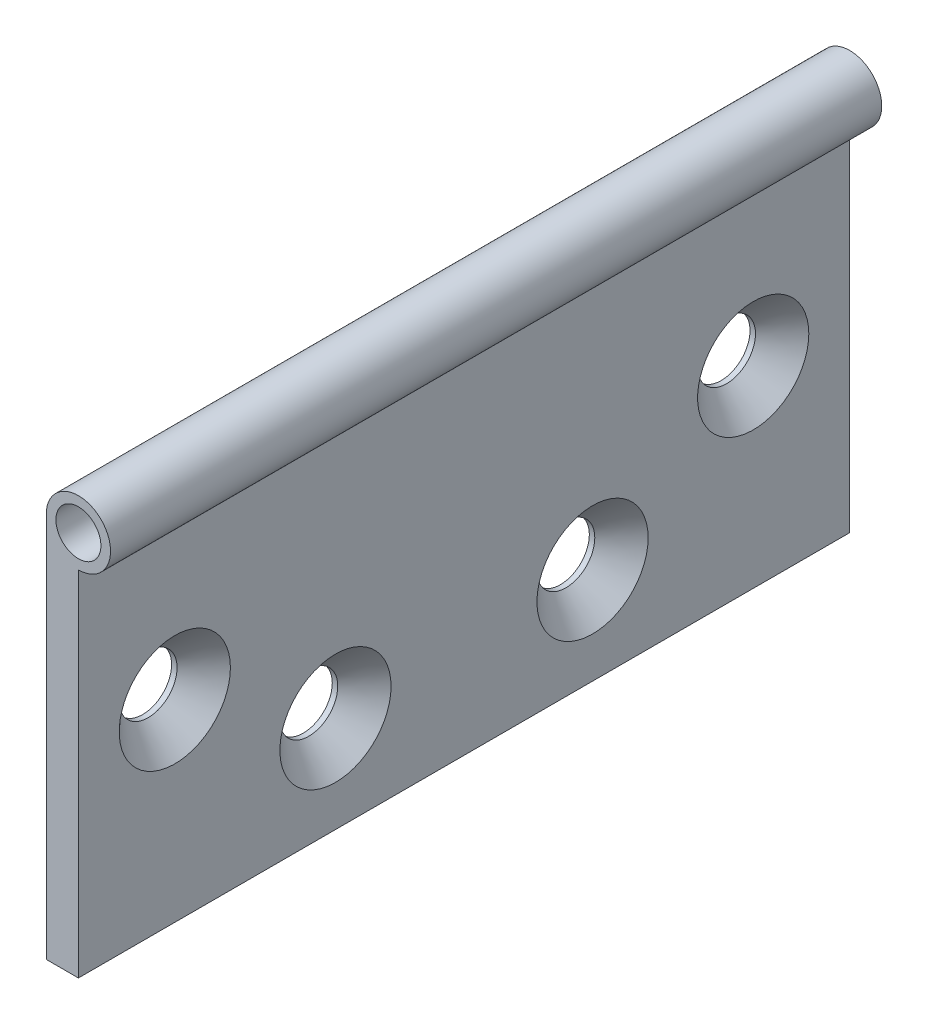
SolidWorks part; units mm, degrees
ref_plane "Front Plane" through (0, 0, 0) normal (0, 0, 1) x (1, 0, 0)
ref_plane "Top Plane" through (0, 0, 0) normal (0, 1, 0) x (1, 0, 0)
ref_plane "Right Plane" through (0, 0, 0) normal (1, 0, 0) x (0, 0, -1)
sketch "Эскиз1" plane through (0, 0, 0) normal (0, 0, 1) x (1, 0, 0)
  line L0 (0, 0) -> (0, 60)
  dimension "D1" = 60
extrude "Вытянуть-Тонкостенный1" add sketch "Эскиз1" along normal mid plane 120 thin
sketch "Эскиз2" plane through (0, 0, 60) normal (0, 0, 1) x (1, 0, 0)
  circle A0 centre (5, 60) radius 5
sweep "По траектории1" add profiles "Эскиз2" path edge at (5, 60, 0)
sketch "Эскиз4" plane through (0, 0, 60) normal (0, 0, 1) x (1, 0, 0)
  circle A0 centre (5, 60) radius 3.5
  arc A1 (5, 55) -> (0, 60) centre (5, 60) ccw construction
extrude "Вырез-Вытянуть1" cut sketch "Эскиз4" against normal through all
hole_wizard "Зенковка для  винта с плоской головкой M81" positions "Эскиз6" profile "Эскиз5" countersink size "M8" standard "Ansi Metric" end condition through all
sketch "Эскиз6" plane through (5, 0, 0) normal (1, 0, 0) x (0, 0, -1)
  point P0 (-45, 30)
  point P2 (-20, 15)
  dimension "D1" = 30
  dimension "D2" = 15
  dimension "D3" = 15
  dimension "D4" = 40
sketch "Эскиз5" plane through (5, 30, 45) normal (0, 1, 0) x (0, 0, -1)
  line L0 (0, 0) -> (0, 5)
  line L1 (0, 5) -> (4.5, 5)
  line L2 (4.5, 5) -> (4.5, 4.15)
  line L3 (4.5, 4.15) -> (8.65, 0)
  line L5 (8.65, 0) -> (0, 0)
  line L6 (-4.5, 4.15) -> (-8.65, 0) construction
  line L11 (0, -6.35) -> (0, 107.95) construction
  dimension "Диаметр сквозного отверстия" = 9
  dimension "Глубина сквозного отверстия" = 5
  dimension "Диаметр передней зенковки" = 17.3
  dimension "Угол передней зенковки" = 90
mirror "Зеркальное отражение1" about plane through (0, 0, 0) normal (0, 0, 1) of "Зенковка для  винта с плоской головкой M81"
sketch "компоновка для вырезов" plane through (5, 0, 0) normal (1, 0, 0) x (0, 0, -1)
  line L0 (-60, 65) -> (-60, 55) construction
  line L1 (60, 55) -> (60, 65) construction
  line L2 (-60, 65) -> (-60, 54)
  line L3 (60, 54) -> (-60, 54)
  line L4 (60, 54) -> (-60, 54)
  line L5 (60, 54) -> (60, 65)
  line L6 (-36, 65) -> (-36, 54)
  line L7 (60, 65) -> (-60, 65) construction
  line L8 (-12, 65) -> (-12, 54)
  line L9 (0, 81.1737) -> (0, 0) construction
  line L10 (12, 65) -> (12, 54)
  line L11 (36, 65) -> (36, 54)
  dimension "D2" = 24
  dimension "D3" = 24
  dimension "D1" = 1
equation "\"D1@Эскиз6\"= \"D1@Эскиз1\" / 2"
equation "\"D4@Эскиз6\"= \"D1@Вытянуть-Тонкостенный1\" / 3"
equation "\"D2@компоновка для вырезов\"= \"D1@Вытянуть-Тонкостенный1\"/5"
equation "\"D3@компоновка для вырезов\"= \"D1@Вытянуть-Тонкостенный1\" / 5"
